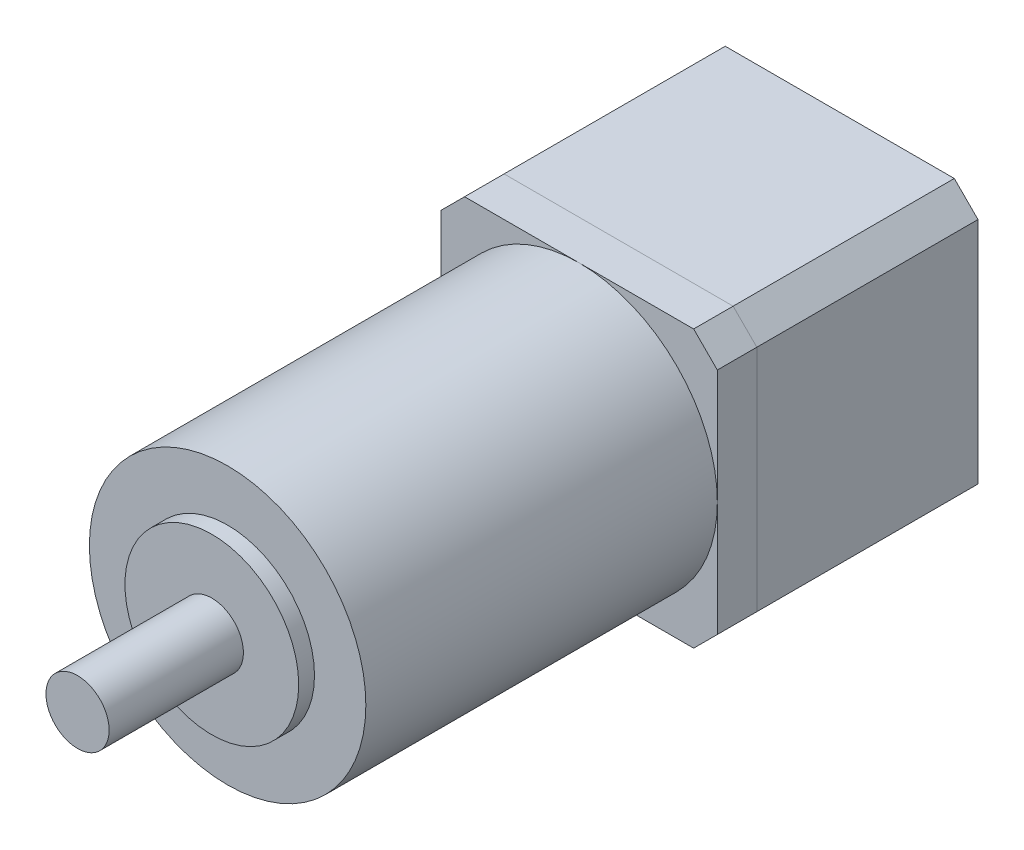
SolidWorks part; units mm, degrees
ref_plane "Front Plane" through (0, 0, 0) normal (0, 0, 1) x (1, 0, 0)
ref_plane "Top Plane" through (0, 0, 0) normal (0, 1, 0) x (1, 0, 0)
ref_plane "Right Plane" through (0, 0, 0) normal (1, 0, 0) x (0, 0, -1)
sketch "Sketch1" plane through (0, 0, 0) normal (0, 0, 1) x (1, 0, 0)
  line L1 (-17.5, 17.5) -> (17.5, 17.5)
  line L2 (-17.5, 17.5) -> (-17.5, -17.5)
  line L3 (-17.5, -17.5) -> (17.5, -17.5)
  line L4 (17.5, 17.5) -> (17.5, -17.5)
  line L5 (-17.5, 17.5) -> (17.5, -17.5) construction
  line L6 (-17.5, -17.5) -> (17.5, 17.5) construction
  point P0 (0, 0)
  dimension "D1" = 35
  dimension "D2" = 35
extrude "Boss-Extrude1" add sketch "Sketch1" along normal blind 28
chamfer "Chamfer1" distance 3 angle 45 4 edges at (17.5, -17.5, 14) (-17.5, -17.5, 14) (17.5, 17.5, 14) (-17.5, 17.5, 14)
sketch "Sketch2" plane through (0, 0, 28) normal (0, 0, 1) x (1, 0, 0)
  line L8 (-14.5, -17.5) -> (14.5, -17.5)
  line L9 (14.5, -17.5) -> (17.5, -14.5)
  line L10 (17.5, -14.5) -> (17.5, 14.5)
  line L11 (17.5, 14.5) -> (14.5, 17.5)
  line L12 (14.5, 17.5) -> (-14.5, 17.5)
  line L13 (-14.5, 17.5) -> (-17.5, 14.5)
  line L14 (-17.5, 14.5) -> (-17.5, -14.5)
  line L15 (-17.5, -14.5) -> (-14.5, -17.5)
  line L16 (-14.5, -17.5) -> (14.5, -17.5)
  line L17 (14.5, -17.5) -> (17.5, -14.5)
  line L18 (17.5, -14.5) -> (17.5, 14.5)
  line L19 (17.5, 14.5) -> (14.5, 17.5)
  line L20 (14.5, 17.5) -> (-14.5, 17.5)
  line L21 (-14.5, 17.5) -> (-17.5, 14.5)
  line L22 (-17.5, 14.5) -> (-17.5, -14.5)
  line L23 (-17.5, -14.5) -> (-14.5, -17.5)
  dimension "D1" = 0
extrude "Boss-Extrude2" add sketch "Sketch2" along normal blind 5 separate body
sketch "Sketch3" plane through (0, 0, 33) normal (0, 0, 1) x (1, 0, 0)
  circle A0 centre (0, 0) radius 17.5
  dimension "D1" = 35
extrude "Boss-Extrude3" add sketch "Sketch3" along normal blind 44.5 separate body
sketch "Sketch4" plane through (0, 0, 77.5) normal (0, 0, 1) x (1, 0, 0)
  circle A0 centre (0, 0) radius 11
  dimension "D1" = 22
extrude "Boss-Extrude4" add sketch "Sketch4" along normal blind 2
sketch "Sketch5" plane through (0, 0, 79.5) normal (0, 0, 1) x (1, 0, 0)
  circle A0 centre (0, 0) radius 4
  dimension "D1" = 8
extrude "Boss-Extrude5" add sketch "Sketch5" along normal blind 17 separate body
